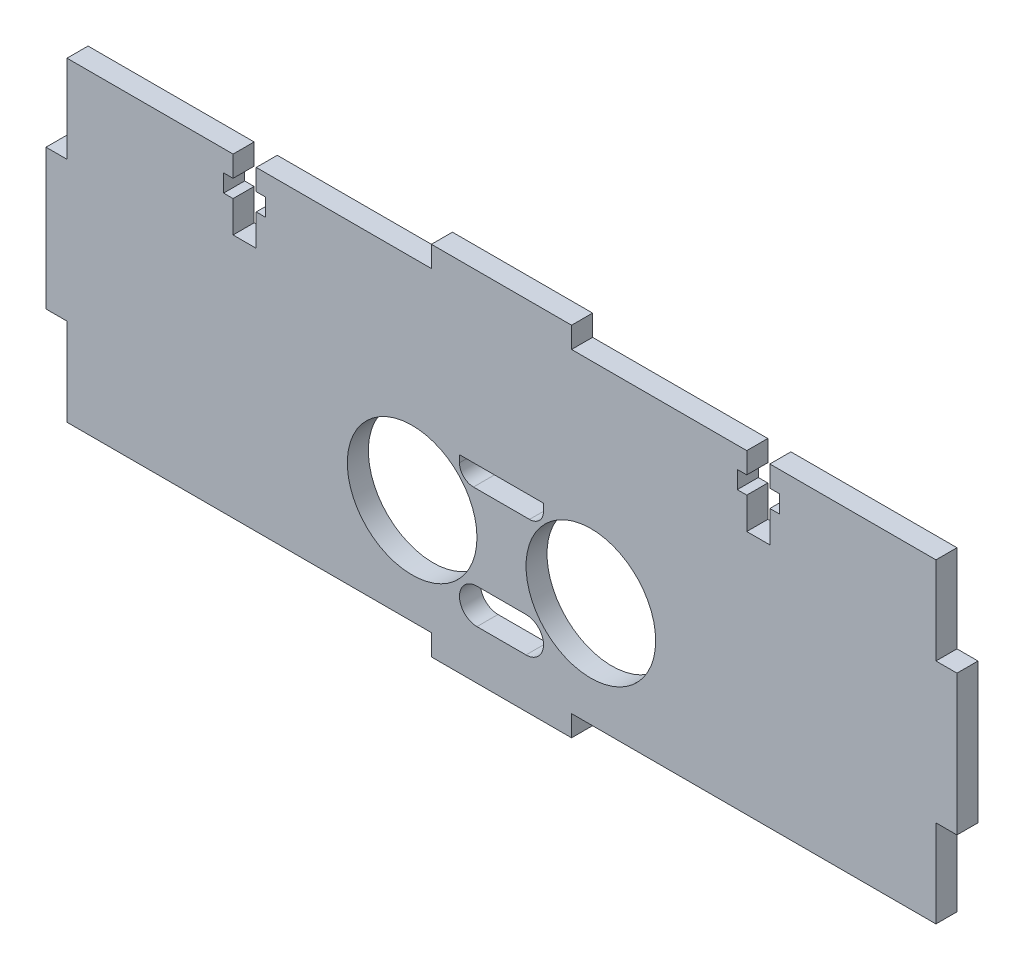
SolidWorks part; units mm, degrees
ref_plane "Front Plane" through (0, 0, 0) normal (0, 0, 1) x (1, 0, 0)
ref_plane "Top Plane" through (0, 0, 0) normal (0, 1, 0) x (1, 0, 0)
ref_plane "Right Plane" through (0, 0, 0) normal (1, 0, 0) x (0, 0, -1)
sketch "Sketch1" plane through (0, 0, 0) normal (0, 0, 1) x (1, 0, 0)
  line L0 (-3.5, -16) -> (3.5, -16) construction
  line L1 (62, -22.5) -> (-62, -22.5)
  line L2 (62, -22.5) -> (62, 22.5)
  line L3 (62, 22.5) -> (-62, 22.5)
  line L4 (-62, -22.5) -> (-62, 22.5)
  line L5 (62, -22.5) -> (-62, 22.5) construction
  line L6 (62, 22.5) -> (-62, -22.5) construction
  line L7 (-3.5, -13.5) -> (3.5, -13.5)
  line L8 (-3.5, -18.5) -> (3.5, -18.5)
  line L9 (0, -55) -> (0, 55) construction
  line L10 (4, -1.5) -> (-4, -1.5)
  line L11 (6, 0.5) -> (6, 1.5)
  line L12 (6, 1.5) -> (-6, 1.5)
  line L13 (-6, 0.5) -> (-6, 1.5)
  line L14 (6, -1.5) -> (-6, 1.5) construction
  line L15 (6, 1.5) -> (-6, -1.5) construction
  line L16 (10, -25.5) -> (-10, -25.5)
  line L17 (10, -25.5) -> (10, -22.5)
  line L18 (10, -22.5) -> (-10, -22.5)
  line L19 (-10, -25.5) -> (-10, -22.5)
  line L20 (10, -25.5) -> (-10, -22.5) construction
  line L21 (10, -22.5) -> (-10, -25.5) construction
  line L22 (-65, -10) -> (-62, -10)
  line L23 (-65, -10) -> (-65, 10)
  line L24 (-65, 10) -> (-62, 10)
  line L25 (-62, -10) -> (-62, 10)
  line L26 (-65, -10) -> (-62, 10) construction
  line L27 (-65, 10) -> (-62, -10) construction
  line L28 (65, 10) -> (62, 10)
  line L29 (62, -10) -> (62, 10)
  line L30 (65, -10) -> (62, -10)
  line L31 (65, -10) -> (65, 10)
  line L32 (55, 0) -> (-55, 0) construction
  line L33 (10, 22.5) -> (-10, 22.5)
  line L34 (-10, 25.5) -> (-10, 22.5)
  line L35 (10, 25.5) -> (-10, 25.5)
  line L36 (10, 25.5) -> (10, 22.5)
  line L37 (33.65, 17) -> (39.65, 17)
  line L38 (-35, 12.5) -> (-38.3, 12.5)
  line L39 (-35, 12.5) -> (-35, 22.5)
  line L40 (-35, 22.5) -> (-38.3, 22.5)
  line L41 (-38.3, 12.5) -> (-38.3, 22.5)
  line L42 (-35, 12.5) -> (-38.3, 22.5) construction
  line L43 (-35, 22.5) -> (-38.3, 12.5) construction
  line L44 (-33.65, 19.5) -> (-39.65, 19.5)
  line L45 (-33.65, 19.5) -> (-33.65, 17)
  line L46 (-33.65, 17) -> (-39.65, 17)
  line L47 (-39.65, 19.5) -> (-39.65, 17)
  line L48 (-33.65, 19.5) -> (-39.65, 17) construction
  line L49 (-33.65, 17) -> (-39.65, 19.5) construction
  line L50 (39.65, 19.5) -> (39.65, 17)
  line L51 (33.65, 19.5) -> (39.65, 19.5)
  line L52 (33.65, 19.5) -> (33.65, 17)
  line L53 (35, 22.5) -> (38.3, 22.5)
  line L54 (38.3, 12.5) -> (38.3, 22.5)
  line L55 (35, 12.5) -> (38.3, 12.5)
  line L56 (35, 12.5) -> (35, 22.5)
  circle A0 centre (-12.75, -7.5) radius 9.25
  circle A1 centre (12.75, -7.5) radius 9.25
  arc A2 (-3.5, -13.5) -> (-3.5, -18.5) centre (-3.5, -16) ccw
  arc A3 (3.5, -18.5) -> (3.5, -13.5) centre (3.5, -16) ccw
  arc A4 (4, -1.5) -> (6, 0.5) centre (4, 0.5) ccw
  arc A5 (-4, -1.5) -> (-6, 0.5) centre (-4, 0.5) cw
  point P0 (0, 0)
  point P10 (0, -16)
  point P17 (-36.65, 17.5)
  point P18 (-63.5, 0)
  point P19 (0, 0)
  point P31 (0, -24)
  point P55 (-36.65, 18.25)
  dimension "D3" = 18.5
  dimension "D8" = 2.5
  dimension "D13" = 2
  dimension "D1" = 124
  dimension "D2" = 45
  dimension "D4" = 25.5
  dimension "D5" = 15
  dimension "D6" = 12.75
  dimension "D7" = 7
  dimension "D9" = 6
  dimension "D10" = 6
  dimension "D11" = 3
  dimension "D12" = 12
  dimension "D14" = 20
  dimension "D15" = 3
  dimension "D16" = 20
  dimension "D17" = 3
  dimension "D18" = 3.3
  dimension "D19" = 10
  dimension "D20" = 6
  dimension "D21" = 2.5
  dimension "D22" = 3
  dimension "D23" = 25
extrude "Boss-Extrude1" add sketch "Sketch1" along normal blind 3 contours L24 L23 L22 L4 | L4 L1 L2 L3 A3 L8 A2 L7 A1 A0 L10 A5 L13 L12 L11 A4 | L36 L35 L34 L3 | L30 L31 L28 L2 | L19 L16 L17 L1
